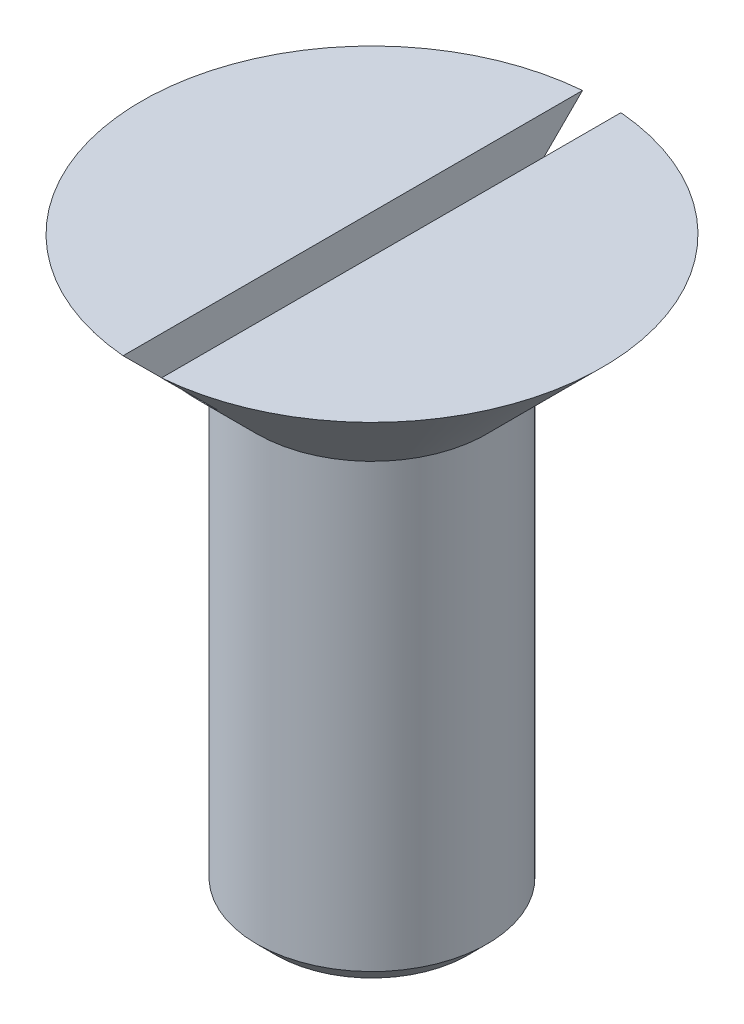
SolidWorks part; units mm, degrees
ref_plane "Front Plane" through (0, 0, 0) normal (0, 0, 1) x (1, 0, 0)
ref_plane "Top Plane" through (0, 0, 0) normal (0, 1, 0) x (1, 0, 0)
ref_plane "Right Plane" through (0, 0, 0) normal (1, 0, 0) x (0, 0, -1)
sketch "Sketch1" plane through (0, 0, 0) normal (0, 0, 1) x (1, 0, 0)
  line L0 (0, 23.3313) -> (0, -22.3997) construction
  line L1 (0, 0) -> (5, 0)
  line L2 (6, 1) -> (6, 24)
  line L3 (6, 24) -> (12, 30)
  line L4 (12, 30) -> (0, 30)
  line L5 (0, 0) -> (0, 30)
  line L7 (5, 0) -> (6, 1)
  line L8 (0, 0) -> (0, 33.3673) construction
  point P4 (6, 0)
  dimension "D1" = 12
  dimension "D2" = 6
  dimension "D3" = 6
  dimension "D5" = 30
  dimension "D7" = 1
  dimension "D8" = 45
revolve "Revolve1" add sketch "Sketch1" angle 360 about L0
sketch "Sketch2" plane through (0, 0, 0) normal (0, 0, 1) x (1, 0, 0)
  line L0 (12, 30) -> (-12, 30) construction
  line L1 (-1, 33) -> (1, 33)
  line L2 (-1, 33) -> (-1, 27)
  line L3 (-1, 27) -> (1, 27)
  line L4 (1, 33) -> (1, 27)
  line L5 (-1, 33) -> (1, 27) construction
  line L6 (-1, 27) -> (1, 33) construction
  point P0 (0, 30)
  dimension "D1" = 3
  dimension "D2" = 2
extrude "Cut-Extrude1" cut sketch "Sketch2" against normal through all both and the other way through all
